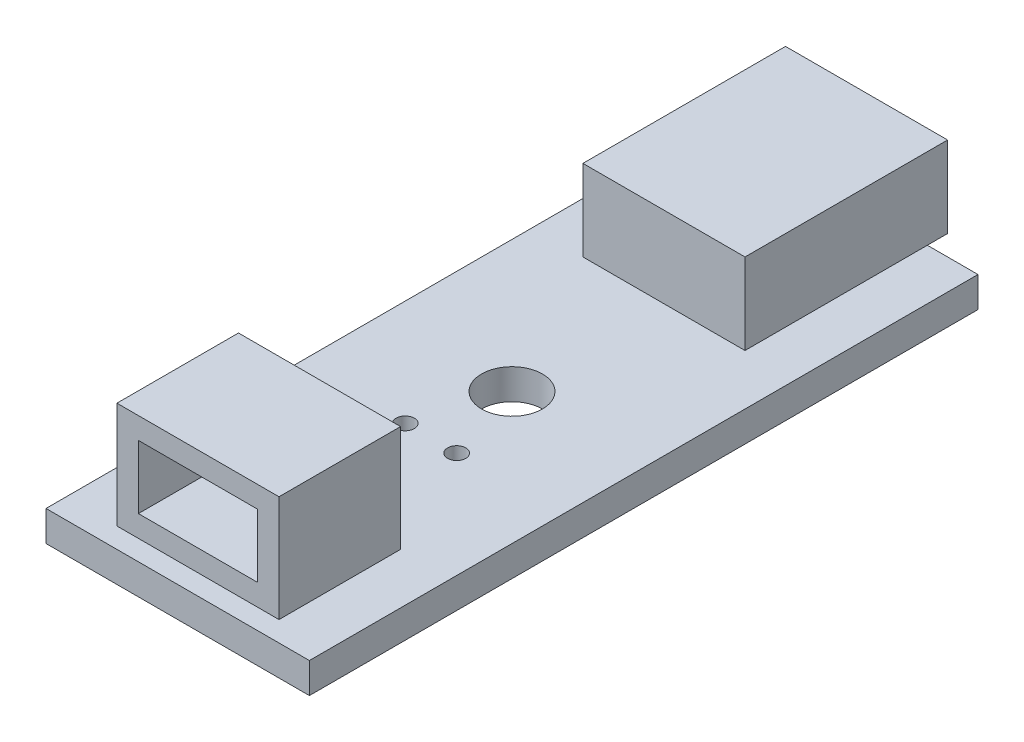
SolidWorks part; units mm, degrees
material "Custom Plastic"
ref_plane "Front Plane" through (0, 0, 0) normal (0, 0, 1) x (1, 0, 0)
ref_plane "Top Plane" through (0, 0, 0) normal (0, 1, 0) x (1, 0, 0)
ref_plane "Right Plane" through (0, 0, 0) normal (1, 0, 0) x (0, 0, -1)
sketch "Sketch2" plane through (0, 0, 0) normal (0, 1, 0) x (1, 0, 0)
  line L1 (-6.5, -16.5) -> (6.5, -16.5)
  line L2 (-6.5, -16.5) -> (-6.5, 16.5)
  line L3 (-6.5, 16.5) -> (6.5, 16.5)
  line L4 (6.5, -16.5) -> (6.5, 16.5)
  point P0 (0, 0)
extrude "Boss-Extrude1" add sketch "Sketch2" along normal blind 1.5
sketch "Sketch3" plane through (0, 1.5, 0) normal (0, 1, 0) x (1, 0, 0)
  line L3 (-4, -15.5) -> (4, -15.5)
  line L4 (-4, -15.5) -> (-4, -9.5)
  line L5 (-4, -9.5) -> (4, -9.5)
  line L6 (4, -15.5) -> (4, -9.5)
extrude "Boss-Extrude2" add sketch "Sketch3" along normal blind 5.25
sketch "Sketch4" plane through (0, 0, 15.5) normal (0, 0, 1) x (1, 0, 0)
  line L3 (-2.9393, 5.6893) -> (2.9393, 5.6893)
  line L4 (-2.9393, 5.6893) -> (-2.9393, 2.5607)
  line L5 (-2.9393, 2.5607) -> (2.9393, 2.5607)
  line L6 (2.9393, 5.6893) -> (2.9393, 2.5607)
extrude "Cut-Extrude1" cut sketch "Sketch4" against normal blind 5
sketch "Sketch5" plane through (0, 1.5, 0) normal (0, 1, 0) x (1, 0, 0)
  circle A0 centre (0, 0) radius 1.5
extrude "Cut-Extrude2" cut sketch "Sketch5" against normal blind 7
sketch "Sketch6" plane through (0, 1.5, 0) normal (0, 1, 0) x (1, 0, 0)
  circle A0 centre (-1.27, -4) radius 0.45
  circle A1 centre (1.27, -4) radius 0.45
extrude "Cut-Extrude3" cut sketch "Sketch6" against normal blind 7
sketch "Sketch7" plane through (0, 1.5, 0) normal (0, 1, 0) x (1, 0, 0)
  line L3 (4, 7.5) -> (-4, 7.5)
  line L4 (4, 7.5) -> (4, 16.5)
  line L5 (4, 16.5) -> (-4, 16.5)
  line L6 (-4, 7.5) -> (-4, 16.5)
extrude "Boss-Extrude3" add sketch "Sketch7" along normal blind 4
sketch "Sketch10" plane through (0, 0, -16.5) normal (0, 0, -1) x (-1, 0, 0)
  line L1 (-4, 5.5) -> (4, 5.5)
  line L2 (-4, 5.5) -> (-4, 1.5)
  line L3 (-4, 1.5) -> (4, 1.5)
  line L4 (4, 5.5) -> (4, 1.5)
extrude "Boss-Extrude5" add sketch "Sketch10" along normal blind 1
sketch "Sketch12" plane through (0, 0, -17.5) normal (0, 0, -1) x (-1, 0, 0)
  line L3 (-3.4908, 5.0091) -> (3.5092, 5.0091)
  line L4 (3.5092, 5.0091) -> (3.5092, 3.7591)
  line L5 (3.5092, 3.7591) -> (3.0092, 3.0091)
  line L6 (3.0092, 3.0091) -> (3.0092, 2.0091)
  line L7 (-3.4908, 5.0091) -> (-3.4908, 3.7591)
  line L8 (-3.4908, 3.7591) -> (-2.9908, 3.0091)
  line L9 (-2.9908, 3.0091) -> (-2.9908, 2.0091)
  line L10 (-2.9908, 2.0091) -> (3.0092, 2.0091)
extrude "Cut-Extrude5" cut sketch "Sketch12" against normal blind 5
